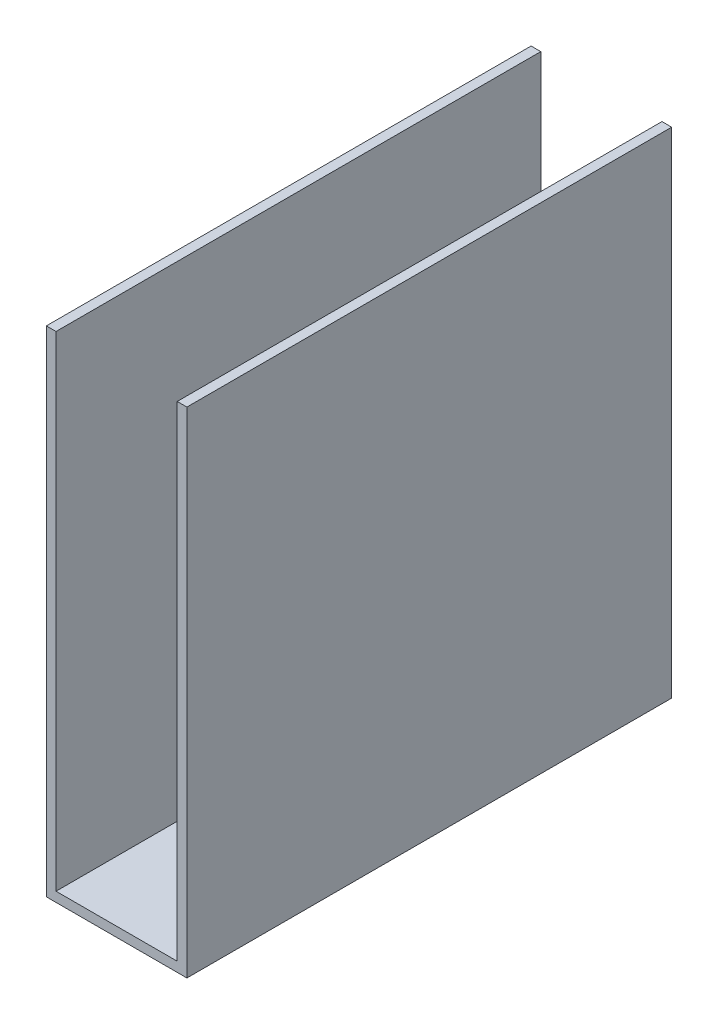
SolidWorks part; units mm, degrees
ref_plane "Front Plane" through (0, 0, 0) normal (0, 0, 1) x (1, 0, 0)
ref_plane "Top Plane" through (0, 0, 0) normal (0, 1, 0) x (1, 0, 0)
ref_plane "Right Plane" through (0, 0, 0) normal (1, 0, 0) x (0, 0, -1)
sketch "Sketch2" plane through (0, 0, 0) normal (0, 0, 1) x (1, 0, 0)
  line L0 (0, 0) -> (0, -10000)
  line L1 (0, -10000) -> (2500, -10000)
  line L2 (2500, -10000) -> (2500, 0)
  line L3 (-200, 0) -> (-200, -10200)
  line L4 (-200, -10200) -> (2700, -10200)
  line L5 (2700, -10200) -> (2700, 0)
  line L6 (-200, 0) -> (0, 0)
  line L7 (2500, 0) -> (2700, 0)
extrude "Boss-Extrude1" add sketch "Sketch2" against normal blind 10000
